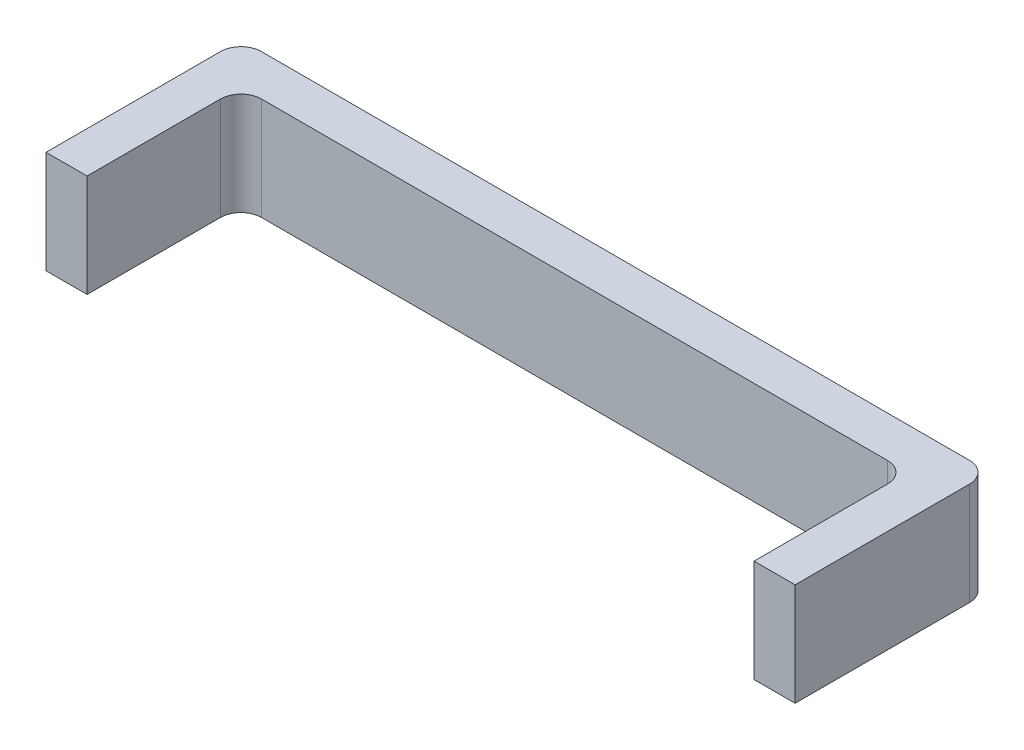
SolidWorks part; units mm, degrees
ref_plane "Front Plane" through (0, 0, 0) normal (0, 0, 1) x (1, 0, 0)
ref_plane "Top Plane" through (0, 0, 0) normal (0, 1, 0) x (1, 0, 0)
ref_plane "Right Plane" through (0, 0, 0) normal (1, 0, 0) x (0, 0, -1)
sketch "Sketch1" plane through (0, 0, 0) normal (0, 1, 0) x (1, 0, 0)
  line L0 (-32.5, 0) -> (32.5, 0)
  line L1 (32.5, 0) -> (32.5, -15)
  line L2 (32.5, -15) -> (36.5, -15)
  line L3 (36.5, -15) -> (36.5, 4)
  line L4 (36.5, 4) -> (-36.5, 4)
  line L5 (-36.5, 4) -> (-36.5, -15)
  line L6 (-36.5, -15) -> (-32.5, -15)
  line L7 (-32.5, -15) -> (-32.5, 0)
  point P4 (0, 0)
  dimension "D1" = 65
  dimension "D2" = 15
  dimension "D3" = 4
  dimension "D4" = 4
extrude "Boss-Extrude1" add sketch "Sketch1" along normal blind 10
fillet "Fillet1" radius 2 4 edges at (-36.5, 5, -4) (-32.5, 5, 0) (32.5, 5, 0) (36.5, 5, -4)
